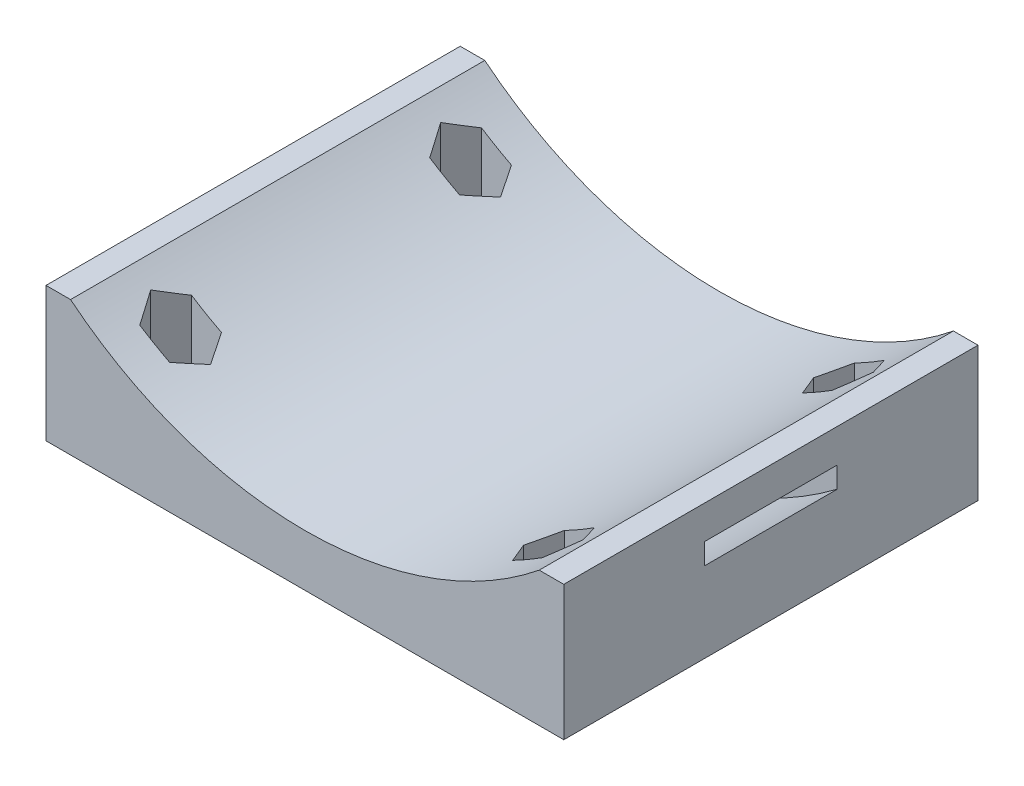
SolidWorks part; units mm, degrees
ref_plane "Front Plane" through (0, 0, 0) normal (0, 0, 1) x (1, 0, 0)
ref_plane "Top Plane" through (0, 0, 0) normal (0, 1, 0) x (1, 0, 0)
ref_plane "Right Plane" through (0, 0, 0) normal (1, 0, 0) x (0, 0, -1)
sketch "Sketch1" plane through (0, 0, 0) normal (0, 0, 1) x (1, 0, 0)
  line L2 (-39.6875, -3.0221) -> (-39.6875, -26.9875)
  line L3 (-39.6875, -26.9875) -> (39.6875, -26.9875)
  line L4 (39.6875, -3.0221) -> (39.6875, -26.9875)
  line L5 (0, 0) -> (39.6875, -26.9875) construction
  line L6 (-39.6875, -26.9875) -> (0, 0) construction
  arc A0 (-39.6875, -3.0221) -> (39.6875, -3.0221) centre (0, 38.1) ccw
  point P0 (0, 0)
  dimension "D2" = 114.3
  dimension "D1" = 79.375
  dimension "D3" = 38.1
  dimension "D4" = 26.9875
extrude "Boss-Extrude1" add sketch "Sketch1" along normal blind 63.5
sketch "Sketch2" plane through (0, 0, 63.5) normal (0, 0, 1) x (1, 0, 0)
  line L1 (63.5, 6.35) -> (-63.5, 6.35)
  line L2 (63.5, 6.35) -> (63.5, -6.35)
  line L3 (63.5, -6.35) -> (-63.5, -6.35)
  line L4 (-63.5, 6.35) -> (-63.5, -6.35)
  line L5 (63.5, 6.35) -> (-63.5, -6.35) construction
  line L6 (63.5, -6.35) -> (-63.5, 6.35) construction
  point P0 (0, 0)
  dimension "D1" = 12.7
  dimension "D2" = 127
extrude "Cut-Extrude1" cut sketch "Sketch2" against normal through all
sketch "Sketch3" plane through (0, 0, 0) normal (1, 0, 0) x (0, 0, -1)
  line L0 (-16.4047, 38.1) -> (-44.1453, 38.1) construction
  line L1 (0, -26.9875) -> (0, -6.35) construction
  line L2 (-41.91, -25.4) -> (-21.59, -25.4)
  line L3 (-41.91, -25.4) -> (-41.91, -27.94)
  line L4 (-41.91, -27.94) -> (-21.59, -27.94)
  line L5 (-21.59, -25.4) -> (-21.59, -27.94)
  line L6 (-41.91, -25.4) -> (-21.59, -27.94) construction
  line L7 (-41.91, -27.94) -> (-21.59, -25.4) construction
  point P3 (-31.75, -26.67)
  dimension "D1" = 2.54
  dimension "D2" = 20.32
  dimension "D3" = 31.75
  dimension "D4" = 38.1
  dimension "D5" = 64.77
revolve "Cut-Revolve1" cut sketch "Sketch3" angle 360 about L0
hole_wizard "#6 Clearance Hole1" positions "Sketch9" profile "Sketch8" hole size "#6" standard "ANSI Inch" end condition through all
sketch "Sketch9" plane through (0, -26.9875, 0) normal (0, -1, 0) x (-1, 0, 0)
  line L3 (-39.6875, -31.75) -> (39.6875, -31.75) construction
  line L4 (-39.6875, -63.5) -> (-39.6875, 0) construction
  line L5 (39.6875, -63.5) -> (39.6875, 0) construction
  point P0 (-28.575, -9.525)
  point P6 (-28.575, -53.975)
  dimension "D1" = 44.45
  dimension "D2" = 28.575
  dimension "D3" = 22.225
sketch "Sketch8" plane through (28.575, -26.9875, 9.525) normal (1, 0, 0) x (0, 0, -1)
  line L0 (0, 0) -> (0, 20.6375)
  line L1 (0, 20.6375) -> (1.8986, 20.6375)
  line L2 (1.8986, 20.6375) -> (1.8986, 0)
  line L5 (1.8986, 0) -> (0, 0)
  line L11 (0, -6.35) -> (0, 107.95) construction
  dimension "Thru Hole Dia." = 3.7973
  dimension "Thru Hole Depth" = 20.6375
sketch "Sketch10" plane through (0, 0, 0) normal (0, 1, 0) x (1, 0, 0)
  line L1 (23.9923, -9.525) -> (26.2836, -13.4938)
  line L2 (26.2836, -13.4938) -> (30.8664, -13.4938)
  line L3 (30.8664, -13.4938) -> (33.1577, -9.525)
  line L4 (33.1577, -9.525) -> (30.8664, -5.5563)
  line L5 (30.8664, -5.5563) -> (26.2836, -5.5562)
  line L6 (26.2836, -5.5562) -> (23.9923, -9.525)
  line L7 (23.9923, -53.975) -> (26.2836, -57.9437)
  line L8 (26.2836, -57.9437) -> (30.8664, -57.9437)
  line L9 (30.8664, -57.9437) -> (33.1577, -53.975)
  line L10 (33.1577, -53.975) -> (30.8664, -50.0062)
  line L11 (30.8664, -50.0062) -> (26.2836, -50.0062)
  line L12 (26.2836, -50.0062) -> (23.9923, -53.975)
  circle A0 centre (28.575, -9.525) radius 3.9687 construction
  circle A1 centre (28.575, -53.975) radius 3.9687 construction
  dimension "D1" = 7.9375
  dimension "D2" = 7.9375
extrude "Cut-Extrude2" cut sketch "Sketch10" against normal blind 22.225
mirror "Mirror1" about plane through (0, 0, 0) normal (1, 0, 0) of "Cut-Extrude2", "#6 Clearance Hole1"
